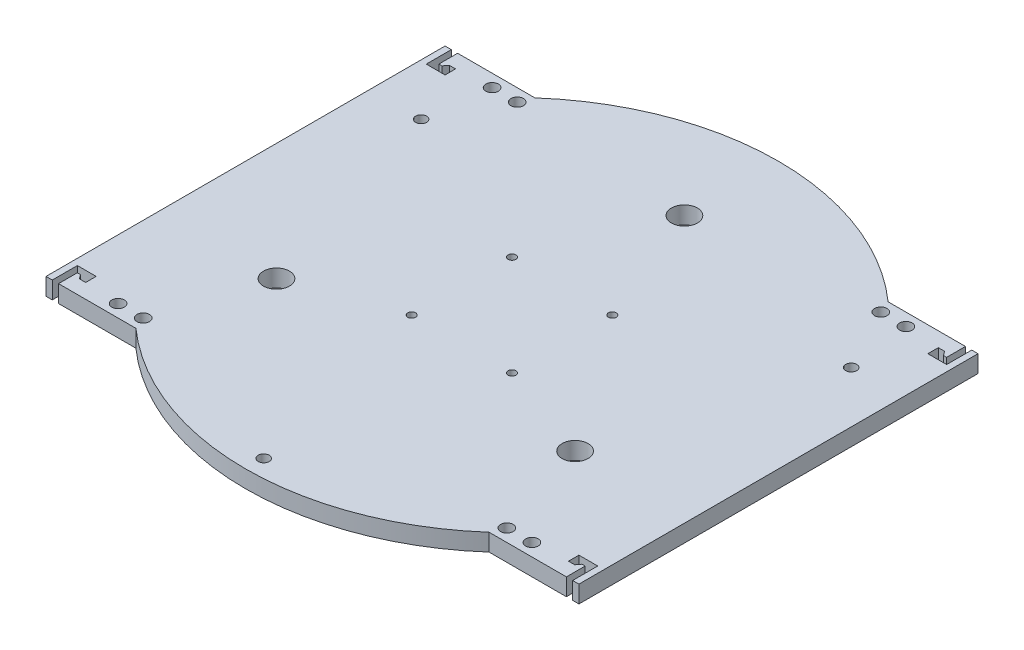
SolidWorks part; units mm, degrees
ref_plane "Front Plane" through (0, 0, 0) normal (0, 0, 1) x (1, 0, 0)
ref_plane "Top Plane" through (0, 0, 0) normal (0, 1, 0) x (1, 0, 0)
ref_plane "Right Plane" through (0, 0, 0) normal (1, 0, 0) x (0, 0, -1)
sketch "Sketch4" plane through (0, 0, 0) normal (0, 1, 0) x (1, 0, 0)
  line L25 (56.3354, 63.65) -> (81, 63.65)
  line L26 (-85, -63.65) -> (-83, -63.65)
  line L31 (-85, -63.65) -> (-85, 63.65)
  line L32 (-85, 63.65) -> (-83, 63.65)
  line L34 (85, -63.65) -> (85, 63.65)
  line L35 (-85, -63.65) -> (85, 63.65) construction
  line L36 (-85, 63.65) -> (85, -63.65) construction
  line L37 (0, 0) -> (0, 85) construction
  line L38 (56.3354, -63.65) -> (81, -63.65)
  line L39 (0, 0) -> (-85, 0) construction
  line L40 (-83, 55.65) -> (-77, 55.65)
  line L41 (-77, 55.65) -> (-77, 58.9927)
  line L43 (-83, 63.65) -> (-83, 55.65)
  line L45 (-81, 63.65) -> (-81, 57.6594)
  line L48 (-81, 57.6594) -> (-80, 57.6594)
  line L50 (-79, 58.9927) -> (-80, 57.6594)
  line L51 (-79, 58.9927) -> (-77, 58.9927)
  line L52 (-81, 63.65) -> (-56.3354, 63.65)
  line L53 (81, 63.65) -> (81, 57.6594)
  line L54 (81, 57.6594) -> (80, 57.6594)
  line L55 (79, 58.9927) -> (80, 57.6594)
  line L56 (79, 58.9927) -> (77, 58.9927)
  line L57 (77, 55.65) -> (77, 58.9927)
  line L58 (83, 55.65) -> (77, 55.65)
  line L59 (83, 63.65) -> (83, 55.65)
  line L60 (-81, -63.65) -> (-81, -57.6594)
  line L61 (-81, -57.6594) -> (-80, -57.6594)
  line L62 (-79, -58.9927) -> (-80, -57.6594)
  line L63 (-79, -58.9927) -> (-77, -58.9927)
  line L64 (-77, -55.65) -> (-77, -58.9927)
  line L65 (-83, -55.65) -> (-77, -55.65)
  line L66 (-83, -63.65) -> (-83, -55.65)
  line L67 (83, -63.65) -> (83, -55.65)
  line L68 (81, -63.65) -> (81, -57.6594)
  line L69 (81, -57.6594) -> (80, -57.6594)
  line L70 (79, -58.9927) -> (80, -57.6594)
  line L71 (79, -58.9927) -> (77, -58.9927)
  line L72 (77, -55.65) -> (77, -58.9927)
  line L73 (83, -55.65) -> (77, -55.65)
  line L74 (83, 63.65) -> (85, 63.65)
  line L75 (83, -63.65) -> (85, -63.65)
  line L76 (-81, -63.65) -> (-56.3354, -63.65)
  arc A36 (-56.3354, -63.65) -> (56.3354, -63.65) centre (0, 0) ccw
  circle A37 centre (0, 0) radius 75 construction
  arc A38 (56.3354, 63.65) -> (-56.3354, 63.65) centre (0, 0) ccw
  circle A47 centre (-58, 59.65) radius 2
  circle A48 centre (-66, 59.65) radius 2
  circle A49 centre (66, 59.65) radius 2
  circle A50 centre (58, 59.65) radius 2
  circle A51 centre (66, -59.65) radius 2
  circle A52 centre (58, -59.65) radius 2
  circle A53 centre (-58, -59.65) radius 2
  circle A54 centre (-66, -59.65) radius 2
  circle A55 centre (-16, 16) radius 1.25
  circle A56 centre (16, 16) radius 1.25
  circle A57 centre (16, -16) radius 1.25
  circle A58 centre (-16, -16) radius 1.25
  circle A59 centre (0, 55) radius 4.15
  circle A60 centre (47.6314, -27.5) radius 4.15
  circle A61 centre (-47.6314, -27.5) radius 4.15
  circle A62 centre (0, -79.1937) radius 1.75
  circle A63 centre (-68.5837, 39.5968) radius 1.75
  circle A64 centre (68.5837, 39.5968) radius 1.75
  point P30 (-58, 59.65)
  point P72 (0, 0)
  point P79 (0, 0)
  point P86 (0, 0)
  dimension "D1" = 150
  dimension "D3" = 127.3
  dimension "D6" = 66
  dimension "D8" = 2
  dimension "D11" = 1.6667
  dimension "D14" = 2.5
  dimension "D4" = 170
  dimension "D13" = 2
  dimension "D10" = 1
  dimension "D2" = 170
  dimension "D5" = 4
  dimension "D15" = 8.3
  dimension "D19" = 3.5
  dimension "D7" = 2
  dimension "D9" = 6
  dimension "D12" = 4
  dimension "D16" = 55
  dimension "D17" = 3
  dimension "D18" = 3
extrude "Boss-Extrude1" add sketch "Sketch4" along normal blind 5.5
